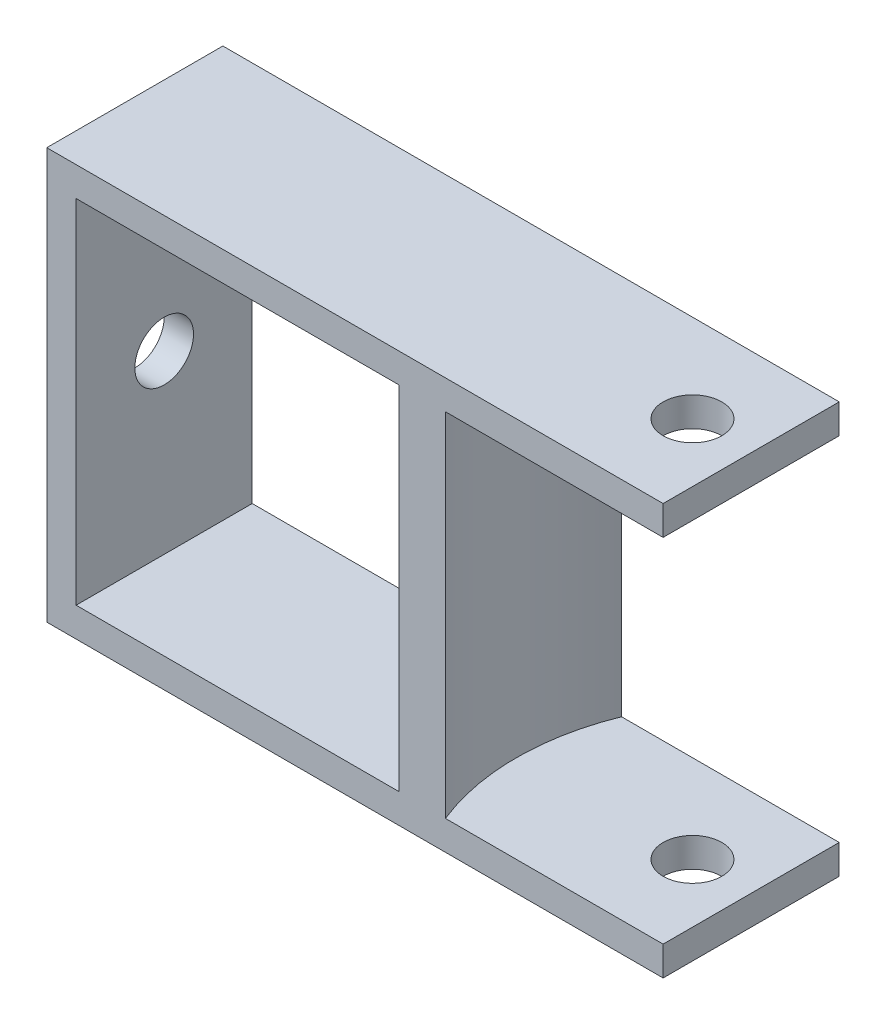
SolidWorks part; units mm, degrees
ref_plane "Alzado" through (0, 0, 0) normal (0, 0, 1) x (1, 0, 0)
ref_plane "Planta" through (0, 0, 0) normal (0, 1, 0) x (1, 0, 0)
ref_plane "Vista lateral" through (0, 0, 0) normal (1, 0, 0) x (0, 0, -1)
sketch "Croquis1" plane through (0, 0, 0) normal (0, 1, 0) x (1, 0, 0)
  line L1 (-38.2353, -8.8911) -> (66.7647, -8.8911)
  line L2 (-38.2353, -8.8911) -> (-38.2353, 21.1089)
  line L3 (-38.2353, 21.1089) -> (66.7647, 21.1089)
  line L4 (66.7647, -8.8911) -> (66.7647, 21.1089)
  circle A2 centre (56.7647, 6.1089) radius 5
  dimension "D3" = 10
  dimension "D4" = 10
  dimension "D1" = 30
  dimension "D2" = 105
  dimension "D5" = 15
extrude "Saliente-Extruir1" add sketch "Croquis1" along normal blind 70
ref_plane "Plano1" through (0, 35, 0) normal (0, -1, 0) x (-1, 0, 0)
sketch "Croquis2" plane through (0, 35, 0) normal (0, -1, 0) x (-1, 0, 0)
  line L0 (-66.7647, -8.8911) -> (-66.7647, 21.1089) construction
  line L1 (38.2353, -8.8911) -> (-66.7647, -8.8911) construction
  circle A0 centre (-66.7647, 6.1089) radius 40
  dimension "D1" = 80
  dimension "D2" = 0
  dimension "D3" = 15
extrude "Cortar-Extruir1" cut sketch "Croquis2" against normal blind 30 and the other way blind 30
sketch "Croquis3" plane through (-38.2353, 0, 0) normal (-1, 0, 0) x (0, 0, 1)
  line L0 (8.8911, 70) -> (8.8911, 0) construction
  line L2 (-21.1089, 0) -> (8.8911, 0) construction
  circle A0 centre (-6.1089, 35) radius 5
  dimension "D1" = 10
  dimension "D2" = 15
  dimension "D3" = 35
extrude "Cortar-Extruir2" cut sketch "Croquis3" against normal blind 30
sketch "Croquis4" plane through (0, 0, 8.8911) normal (0, 0, 1) x (1, 0, 0)
  line L0 (-38.2353, 70) -> (-38.2353, 0) construction
  line L1 (-33.2353, 65) -> (21.7647, 65)
  line L2 (-33.2353, 65) -> (-33.2353, 5)
  line L3 (-33.2353, 5) -> (21.7647, 5)
  line L4 (21.7647, 65) -> (21.7647, 5)
  line L5 (-38.2353, 0) -> (66.7647, 0) construction
  dimension "D1" = 60
  dimension "D2" = 55
  dimension "D3" = 5
  dimension "D4" = 5
extrude "Cortar-Extruir3" cut sketch "Croquis4" against normal blind 30
